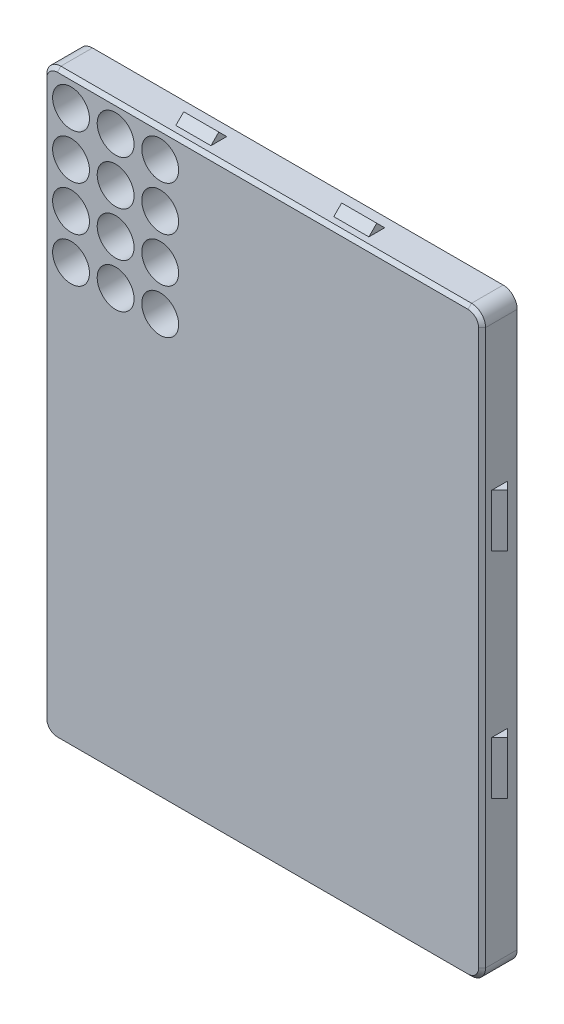
SolidWorks part; units mm, degrees
ref_plane "前视基准面" through (0, 0, 0) normal (0, 0, 1) x (1, 0, 0)
ref_plane "上视基准面" through (0, 0, 0) normal (0, 1, 0) x (1, 0, 0)
ref_plane "右视基准面" through (0, 0, 0) normal (1, 0, 0) x (0, 0, -1)
sketch "草图1" plane through (0, 0, 0) normal (0, 0, 1) x (1, 0, 0)
  line L1 (12.5, -16.6) -> (-12.5, -16.6)
  line L2 (12.5, -16.6) -> (12.5, 16.6)
  line L3 (12.5, 16.6) -> (-12.5, 16.6)
  line L4 (-12.5, -16.6) -> (-12.5, 16.6)
  line L5 (12.5, -16.6) -> (-12.5, 16.6) construction
  line L6 (12.5, 16.6) -> (-12.5, -16.6) construction
  point P0 (0, 0)
  dimension "D1" = 25
  dimension "D2" = 33.2
extrude "凸台-拉伸1" add sketch "草图1" along normal blind 2
fillet "圆角1" radius 0.8 4 edges at (12.5, -16.6, 1) (-12.5, -16.6, 1) (-12.5, 16.6, 1) (12.5, 16.6, 1)
chamfer "倒角1" distance 0.2 angle 45 8 edges at (-12.5, 0, 2) (-12.2657, -16.3657, 2) (-12.2657, 16.3657, 2) (0, -16.6, 2) (0, 16.6, 2) (12.2657, -16.3657, 2) (12.2657, 16.3657, 2) (12.5, 0, 2)
sketch "草图3" plane through (0, 0, 0) normal (0, 0, -1) x (-1, 0, 0)
  line L0 (12.5, 15.8) -> (12.5, -15.8) construction
  line L1 (-11.7, 16.6) -> (11.7, 16.6) construction
  circle A0 centre (10.92, 15.02) radius 1.05
  circle A1 centre (8.38, 15.02) radius 1.05
  circle A2 centre (5.84, 15.02) radius 1.05
  circle A3 centre (8.38, 12.48) radius 1.05
  circle A4 centre (5.84, 12.48) radius 1.05
  circle A5 centre (8.38, 9.94) radius 1.05
  circle A6 centre (5.84, 9.94) radius 1.05
  circle A7 centre (8.38, 7.4) radius 1.05
  circle A8 centre (5.84, 7.4) radius 1.05
  circle A9 centre (10.92, 12.48) radius 1.05
  circle A10 centre (10.92, 9.94) radius 1.05
  circle A11 centre (10.92, 7.4) radius 1.05
  dimension "D1" = 2.1
  dimension "D2" = 1.58
  dimension "D3" = 1.58
  dimension "D4" = 3
  dimension "D5" = 4
extrude "切除-拉伸2" cut sketch "草图3" against normal through all
sketch "草图4" plane through (0, -16.6, 0) normal (0, -1, 0) x (1, 0, 0)
  line L0 (12.5, 1.45) -> (12.95, 1)
  line L1 (12.5, 1.8) -> (12.5, 0) construction
  line L2 (12.95, 1) -> (12.5, 0.55)
  line L3 (12.5, 1.45) -> (12.5, 0.55)
  line L4 (-11.7, 2) -> (11.7, 2) construction
  line L5 (-11.7, 0) -> (11.7, 0) construction
  line L6 (0, 3.8012) -> (0, -2.3615) construction
  line L7 (-12.5, 1.45) -> (-12.95, 1)
  line L8 (-12.95, 1) -> (-12.5, 0.55)
  line L9 (-12.5, 1.45) -> (-12.5, 0.55)
  dimension "D1" = 0.55
  dimension "D2" = 0.55
  dimension "D3" = 90
  dimension "D4" = 45
extrude "凸台-拉伸2" add sketch "草图4" against normal up to surface (33.2 mm away) up to face at (0, 16.6, 0.9)
sketch "草图5" plane through (0, 0, 2) normal (0, 0, 1) x (1, 0, 0)
  line L0 (-12.95, 16.6) -> (-12.95, -16.6) construction
  line L1 (-12.5, 16.6) -> (-12.95, 16.6)
  line L2 (-12.5, 16.6) -> (-12.5, 7.6)
  line L3 (-12.5, 7.6) -> (-12.95, 7.6)
  line L4 (-12.95, 16.6) -> (-12.95, 7.6)
  line L5 (-12.5, -15.8) -> (-12.5, 15.8) construction
  line L6 (-12.95, 4.6) -> (-12.5, 4.6)
  line L7 (-12.95, 4.6) -> (-12.95, -4.6)
  line L8 (-12.95, -4.6) -> (-12.5, -4.6)
  line L9 (-12.5, 4.6) -> (-12.5, -4.6)
  line L10 (0, -1000) -> (0, 49000) construction
  line L11 (-12.5, -16.6) -> (-12.95, -16.6)
  line L12 (-12.5, -16.6) -> (-12.5, -7.6)
  line L13 (-12.5, -7.6) -> (-12.95, -7.6)
  line L14 (-12.95, -16.6) -> (-12.95, -7.6)
  line L15 (12.5, -7.6) -> (12.95, -7.6)
  line L16 (12.95, -16.6) -> (12.95, -7.6)
  line L17 (12.5, -16.6) -> (12.95, -16.6)
  line L18 (12.5, -16.6) -> (12.5, -7.6)
  line L19 (12.95, -4.6) -> (12.5, -4.6)
  line L20 (12.95, 4.6) -> (12.5, 4.6)
  line L21 (12.95, 4.6) -> (12.95, -4.6)
  line L22 (12.5, 4.6) -> (12.5, -4.6)
  line L23 (12.5, 7.6) -> (12.95, 7.6)
  line L24 (12.95, 16.6) -> (12.95, 7.6)
  line L25 (12.5, 16.6) -> (12.95, 16.6)
  line L26 (12.5, 16.6) -> (12.5, 7.6)
  point P18 (-12.725, 4.6)
  dimension "D1" = 9
  dimension "D2" = 3
  dimension "D3" = 9
  dimension "D4" = 3
extrude "切除-拉伸3" cut sketch "草图5" against normal through all both and the other way through all
sketch "草图6" plane through (12.5, 0, 0) normal (1, 0, 0) x (0, 0, -1)
  line L0 (-1.45, 16.6) -> (-0.55, 16.6)
  line L1 (-1.8, 16.6) -> (0, 16.6) construction
  line L2 (-0.55, 16.6) -> (-1, 17.05)
  line L3 (-1, 17.05) -> (-1.45, 16.6)
  line L4 (-2, -15.8) -> (-2, 15.8) construction
  line L5 (0, -15.8) -> (0, 15.8) construction
  line L6 (-1000, 0) -> (49000, 0) construction
  line L7 (-0.55, -16.6) -> (-1, -17.05)
  line L8 (-1.45, -16.6) -> (-0.55, -16.6)
  line L9 (-1, -17.05) -> (-1.45, -16.6)
  dimension "D1" = 0.55
  dimension "D2" = 0.55
  dimension "D3" = 90
  dimension "D4" = 45
extrude "凸台-拉伸3" add sketch "草图6" against normal up to surface (25 mm away)
sketch "草图7" plane through (0, 0, 2) normal (0, 0, 1) x (1, 0, 0)
  line L0 (-1000, 0) -> (49000, 0) construction
  line L1 (-11.7, 16.6) -> (11.7, 16.6) construction
  line L2 (-12.5, 17.05) -> (-5.5, 17.05)
  line L3 (-12.5, 17.05) -> (-12.5, 16.6)
  line L4 (-12.5, 16.6) -> (-5.5, 16.6)
  line L5 (-5.5, 17.05) -> (-5.5, 16.6)
  line L6 (-12.5, 17.05) -> (12.5, 17.05) construction
  line L7 (-3.5, 17.05) -> (3.5, 17.05)
  line L8 (-3.5, 17.05) -> (-3.5, 16.6)
  line L9 (-3.5, 16.6) -> (3.5, 16.6)
  line L10 (3.5, 17.05) -> (3.5, 16.6)
  line L11 (-11.7, 16.6) -> (11.7, 16.6) construction
  line L12 (12.5, -16.6) -> (5.5, -16.6)
  line L13 (12.5, 17.05) -> (5.5, 17.05)
  line L14 (12.5, 17.05) -> (12.5, 16.6)
  line L15 (12.5, 16.6) -> (5.5, 16.6)
  line L16 (5.5, 17.05) -> (5.5, 16.6)
  line L17 (5.5, -17.05) -> (5.5, -16.6)
  line L18 (12.5, -17.05) -> (5.5, -17.05)
  line L19 (12.5, -17.05) -> (12.5, -16.6)
  line L20 (-3.5, -16.6) -> (3.5, -16.6)
  line L21 (3.5, -17.05) -> (3.5, -16.6)
  line L22 (-3.5, -17.05) -> (3.5, -17.05)
  line L23 (-3.5, -17.05) -> (-3.5, -16.6)
  line L24 (-12.5, -16.6) -> (-5.5, -16.6)
  line L25 (-5.5, -17.05) -> (-5.5, -16.6)
  line L26 (-12.5, -17.05) -> (-5.5, -17.05)
  line L27 (-12.5, -17.05) -> (-12.5, -16.6)
  dimension "D1" = 7
  dimension "D2" = 2
  dimension "D3" = 2
  dimension "D4" = 7
extrude "切除-拉伸4" cut sketch "草图7" against normal through all both and the other way through all
